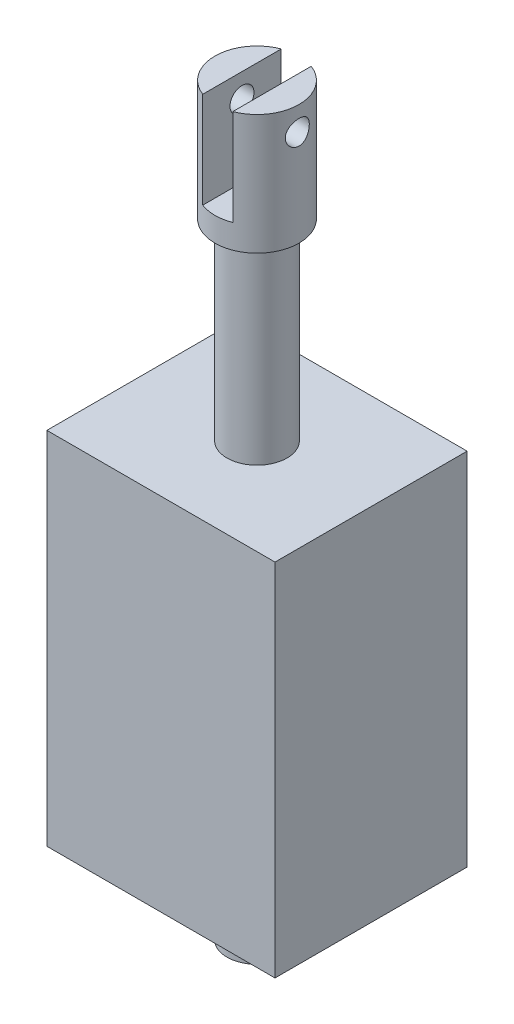
SolidWorks part; units mm, degrees
ref_plane "Front Plane" through (0, 0, 0) normal (0, 0, 1) x (1, 0, 0)
ref_plane "Top Plane" through (0, 0, 0) normal (0, 1, 0) x (1, 0, 0)
ref_plane "Right Plane" through (0, 0, 0) normal (1, 0, 0) x (0, 0, -1)
sketch "Sketch1" plane through (0, 0, 0) normal (0, 1, 0) x (1, 0, 0)
  line L1 (-9.5, -8) -> (9.5, -8)
  line L2 (-9.5, -8) -> (-9.5, 8)
  line L3 (-9.5, 8) -> (9.5, 8)
  line L4 (9.5, -8) -> (9.5, 8)
  line L5 (-9.5, -8) -> (9.5, 8) construction
  line L6 (-9.5, 8) -> (9.5, -8) construction
  point P0 (0, 0)
  dimension "D1" = 19
  dimension "D2" = 16
extrude "Boss-Extrude1" add sketch "Sketch1" along normal blind 30
sketch "Sketch2" plane through (0, 30, 0) normal (0, 1, 0) x (1, 0, 0)
  circle A0 centre (0, 0) radius 3.5
  dimension "D1" = 7
extrude "Boss-Extrude2" add sketch "Sketch2" along normal blind 26
sketch "Sketch3" plane through (0, 0, 0) normal (0, -1, 0) x (1, 0, 0)
  circle A0 centre (0, 0) radius 2.5
  dimension "D1" = 5
extrude "Boss-Extrude3" add sketch "Sketch3" along normal blind 6
sketch "Sketch4" plane through (9.5, 0, 0) normal (1, 0, 0) x (0, 0, -1)
  line L0 (3.5, 56) -> (-3.5, 56) construction
  circle A0 centre (0, 54) radius 1
  point P2 (0, 0)
  dimension "D1" = 2
  dimension "D2" = 2
extrude "Cut-Extrude2" cut sketch "Sketch4" against normal through all
sketch "Sketch5" plane through (0, 30, 0) normal (0, 1, 0) x (1, 0, 0)
  circle A0 centre (0, 0) radius 3.5
  circle A1 centre (0, 0) radius 2.5
  circle A2 centre (0, 0) radius 3.5 construction
  dimension "D1" = 1
extrude "Cut-Extrude3" cut sketch "Sketch5" along normal blind 16 contours A1 | A0
sketch "Sketch6" plane through (0, 0, 0) normal (0, 0, 1) x (1, 0, 0)
  line L0 (3.5, 56) -> (-3.5, 56) construction
  line L1 (-1.25, 56) -> (1.25, 56)
  line L2 (-1.25, 56) -> (-1.25, 48)
  line L3 (-1.25, 48) -> (1.25, 48)
  line L4 (1.25, 56) -> (1.25, 48)
  line L7 (-3.5, 56) -> (3.5, 56) construction
  line L8 (-3.5, 56) -> (-3.5, 55) construction
  line L9 (3.5, 55) -> (3.5, 56) construction
  line L12 (-2.5, 46) -> (2.5, 46) construction
  point P8 (0, 56)
  point P9 (0, 0)
  dimension "D1" = 2.5
  dimension "D2" = 2
extrude "Cut-Extrude4" cut sketch "Sketch6" against normal through all both and the other way through all
